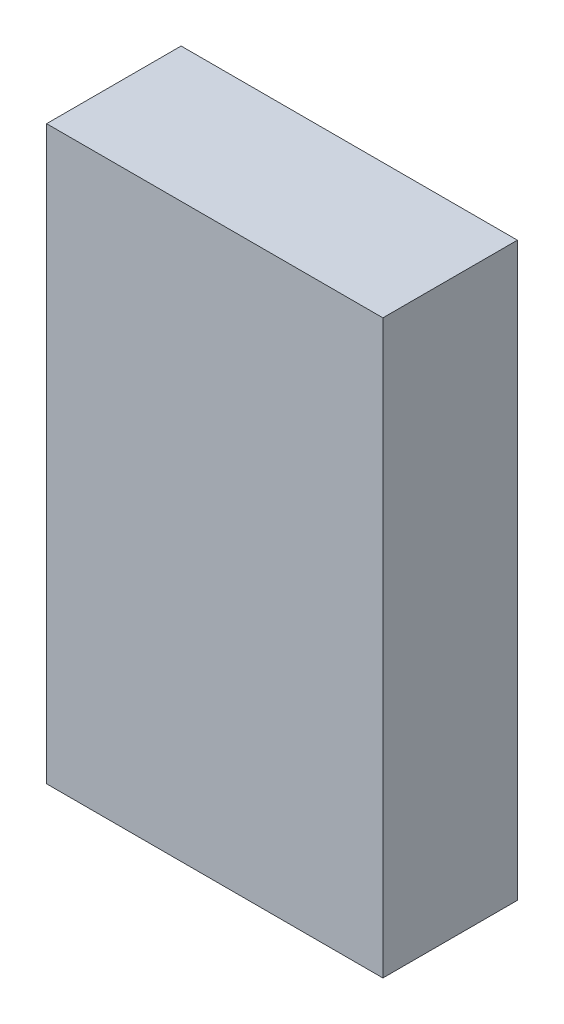
SolidWorks part; units mm, degrees
material "Oak"
ref_plane "Front Plane" through (0, 0, 0) normal (0, 0, 1) x (1, 0, 0)
ref_plane "Top Plane" through (0, 0, 0) normal (0, 1, 0) x (1, 0, 0)
ref_plane "Right Plane" through (0, 0, 0) normal (1, 0, 0) x (0, 0, -1)
sketch "Sketch1" plane through (0, 0, 0) normal (0, 1, 0) x (1, 0, 0)
  line L1 (-25.4, 10.16) -> (25.4, 10.16)
  line L2 (-25.4, 10.16) -> (-25.4, -10.16)
  line L3 (-25.4, -10.16) -> (25.4, -10.16)
  line L4 (25.4, 10.16) -> (25.4, -10.16)
  line L5 (-25.4, 10.16) -> (25.4, -10.16) construction
  line L6 (-25.4, -10.16) -> (25.4, 10.16) construction
  point P0 (0, 0)
  dimension "D1" = 50.8
  dimension "D2" = 20.32
extrude "Boss-Extrude1" add sketch "Sketch1" along normal blind 86.36 contours L1 L4 L3 L2
